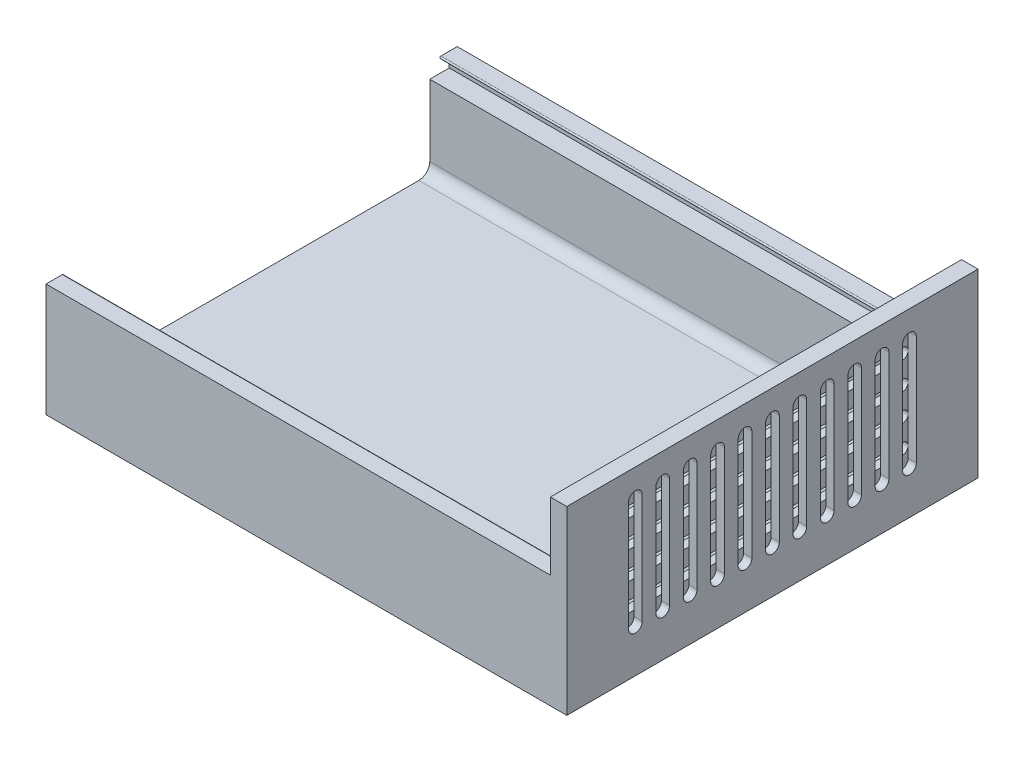
SolidWorks part; units mm, degrees
ref_plane "Front Plane" through (0, 0, 0) normal (0, 0, 1) x (1, 0, 0)
ref_plane "Top Plane" through (0, 0, 0) normal (0, 1, 0) x (1, 0, 0)
ref_plane "Right Plane" through (0, 0, 0) normal (1, 0, 0) x (0, 0, -1)
sketch "Sketch1" plane through (0, 0, 0) normal (0, 1, 0) x (1, 0, 0)
  line L1 (-47.5, -37.5) -> (47.5, -37.5)
  line L2 (-47.5, -37.5) -> (-47.5, 37.5)
  line L3 (-47.5, 37.5) -> (47.5, 37.5)
  line L4 (47.5, -37.5) -> (47.5, 37.5)
  line L5 (-47.5, -37.5) -> (47.5, 37.5) construction
  line L6 (-47.5, 37.5) -> (47.5, -37.5) construction
  point P0 (0, 0)
  dimension "D1" = 95
  dimension "D2" = 75
extrude "Boss-Extrude1" add sketch "Sketch1" along normal blind 3
sketch "Sketch2" plane through (0, 3, 0) normal (0, 1, 0) x (1, 0, 0)
  line L0 (47.5, -37.5) -> (47.5, 37.5) construction
  line L1 (-47.5, 37.5) -> (47.5, 37.5)
  line L2 (-47.5, 37.5) -> (-47.5, 32.5)
  line L3 (-47.5, 32.5) -> (47.5, 32.5)
  line L4 (47.5, 37.5) -> (47.5, 32.5)
  line L6 (-47.5, -37.5) -> (47.5, -37.5)
  line L7 (-47.5, -37.5) -> (-47.5, -32.5)
  line L8 (-47.5, -32.5) -> (47.5, -32.5)
  line L9 (47.5, -37.5) -> (47.5, -32.5)
  dimension "D1" = 5
  dimension "D2" = 5
extrude "Boss-Extrude2" add sketch "Sketch2" along normal blind 15
sketch "Sketch3" plane through (0, 3, 0) normal (0, 1, 0) x (1, 0, 0)
  line L1 (47.5, 37.5) -> (44.5, 37.5)
  line L2 (47.5, 37.5) -> (47.5, -37.5)
  line L3 (47.5, -37.5) -> (44.5, -37.5)
  line L4 (44.5, 37.5) -> (44.5, -37.5)
  line L5 (-47.5, -37.5) -> (47.5, -37.5) construction
  line L6 (47.5, 37.5) -> (-47.5, 37.5) construction
  line L7 (47.5, -32.5) -> (47.5, 32.5) construction
  dimension "D1" = 3
extrude "Boss-Extrude3" add sketch "Sketch3" along normal blind 30
sketch "Sketch4" plane through (47.5, 0, 0) normal (1, 0, 0) x (0, 0, -1)
  line L0 (-37.5, 0) -> (37.5, 0) construction
  line L2 (26.25, 8) -> (26.25, 28)
  line L4 (23.75, 8) -> (23.75, 28)
  line L5 (37.5, 33) -> (37.5, 0) construction
  line L6 (21.25, 8) -> (21.25, 28)
  line L7 (18.75, 8) -> (18.75, 28)
  line L8 (16.25, 8) -> (16.25, 28)
  line L9 (13.75, 8) -> (13.75, 28)
  line L10 (11.25, 8) -> (11.25, 28)
  line L11 (8.75, 8) -> (8.75, 28)
  line L12 (6.25, 8) -> (6.25, 28)
  line L13 (3.75, 8) -> (3.75, 28)
  line L14 (1.25, 8) -> (1.25, 28)
  line L15 (-1.25, 8) -> (-1.25, 28)
  line L16 (-3.75, 8) -> (-3.75, 28)
  line L17 (-6.25, 8) -> (-6.25, 28)
  line L18 (-8.75, 8) -> (-8.75, 28)
  line L19 (-11.25, 8) -> (-11.25, 28)
  line L20 (-13.75, 8) -> (-13.75, 28)
  line L21 (-16.25, 8) -> (-16.25, 28)
  line L22 (-18.75, 8) -> (-18.75, 28)
  line L23 (-21.25, 8) -> (-21.25, 28)
  line L24 (-23.75, 8) -> (-23.75, 28)
  line L25 (-26.25, 8) -> (-26.25, 28)
  arc A0 (26.25, 8) -> (23.75, 8) centre (25, 8) cw
  arc A1 (26.25, 28) -> (23.75, 28) centre (25, 28) ccw
  arc A2 (21.25, 28) -> (18.75, 28) centre (20, 28) ccw
  arc A3 (21.25, 8) -> (18.75, 8) centre (20, 8) cw
  arc A4 (16.25, 28) -> (13.75, 28) centre (15, 28) ccw
  arc A5 (16.25, 8) -> (13.75, 8) centre (15, 8) cw
  arc A6 (11.25, 28) -> (8.75, 28) centre (10, 28) ccw
  arc A7 (11.25, 8) -> (8.75, 8) centre (10, 8) cw
  arc A8 (6.25, 28) -> (3.75, 28) centre (5, 28) ccw
  arc A9 (6.25, 8) -> (3.75, 8) centre (5, 8) cw
  arc A10 (1.25, 28) -> (-1.25, 28) centre (0, 28) ccw
  arc A11 (1.25, 8) -> (-1.25, 8) centre (0, 8) cw
  arc A12 (-3.75, 28) -> (-6.25, 28) centre (-5, 28) ccw
  arc A13 (-3.75, 8) -> (-6.25, 8) centre (-5, 8) cw
  arc A14 (-8.75, 28) -> (-11.25, 28) centre (-10, 28) ccw
  arc A15 (-8.75, 8) -> (-11.25, 8) centre (-10, 8) cw
  arc A16 (-13.75, 28) -> (-16.25, 28) centre (-15, 28) ccw
  arc A17 (-13.75, 8) -> (-16.25, 8) centre (-15, 8) cw
  arc A18 (-18.75, 28) -> (-21.25, 28) centre (-20, 28) ccw
  arc A19 (-18.75, 8) -> (-21.25, 8) centre (-20, 8) cw
  arc A20 (-23.75, 28) -> (-26.25, 28) centre (-25, 28) ccw
  arc A21 (-23.75, 8) -> (-26.25, 8) centre (-25, 8) cw
  dimension "D3" = 8
  dimension "D1" = 2.5
  dimension "D2" = 20
  dimension "D4" = 11.25
  dimension "D5" = 11
extrude "Cut-Extrude1" cut sketch "Sketch4" against normal blind 1.5
sketch "Sketch5" plane through (44.5, 0, 0) normal (-1, 0, 0) x (0, 0, 1)
  line L0 (-26.25, 8) -> (-26.25, 28) construction
  line L1 (-25.25, 24) -> (25.25, 24)
  line L3 (-25.25, 26) -> (25.25, 26)
  line L5 (26.25, 28) -> (26.25, 8) construction
  line L6 (-25.25, 19) -> (25.25, 19)
  line L7 (-25.25, 21) -> (25.25, 21)
  line L8 (-25.25, 14) -> (25.25, 14)
  line L9 (-25.25, 16) -> (25.25, 16)
  line L10 (-25.25, 9) -> (25.25, 9)
  line L11 (-25.25, 11) -> (25.25, 11)
  arc A0 (-25.25, 24) -> (-25.25, 26) centre (-25.25, 25) cw
  arc A1 (25.25, 24) -> (25.25, 26) centre (25.25, 25) ccw
  arc A2 (-3.75, 28) -> (-6.25, 28) centre (-5, 28) ccw construction
  arc A3 (25.25, 19) -> (25.25, 21) centre (25.25, 20) ccw
  arc A4 (-25.25, 19) -> (-25.25, 21) centre (-25.25, 20) cw
  arc A5 (25.25, 14) -> (25.25, 16) centre (25.25, 15) ccw
  arc A6 (-25.25, 14) -> (-25.25, 16) centre (-25.25, 15) cw
  arc A7 (25.25, 9) -> (25.25, 11) centre (25.25, 10) ccw
  arc A8 (-25.25, 9) -> (-25.25, 11) centre (-25.25, 10) cw
  dimension "D1" = 2
  dimension "D2" = 2
  dimension "D3" = 4
extrude "Cut-Extrude2" cut sketch "Sketch5" against normal blind 1.5
sketch "Sketch6" plane through (-47.5, 0, 0) normal (-1, 0, 0) x (0, 0, 1)
  line L0 (37.5, 18) -> (37.5, 20.65)
  line L1 (37.5, 20.65) -> (34.05, 20.65)
  line L3 (34.05, 20.65) -> (36.05, 18.65)
  line L7 (36.05, 18.65) -> (36.05, 18)
  line L8 (32.5, 18) -> (37.5, 18) construction
  line L9 (36.05, 18) -> (37.5, 18)
  line L10 (0, 9.2561) -> (0, -6.358) construction
  line L11 (-36.05, 18) -> (-37.5, 18)
  line L12 (-36.05, 18.65) -> (-36.05, 18)
  line L13 (-34.05, 20.65) -> (-36.05, 18.65)
  line L14 (-37.5, 20.65) -> (-34.05, 20.65)
  line L15 (-37.5, 18) -> (-37.5, 20.65)
  dimension "D1" = 45
  dimension "D2" = 0.65
  dimension "D3" = 1.45
  dimension "D4" = 2.65
extrude "Boss-Extrude4" add sketch "Sketch6" against normal up to surface (95 mm away) up to face at (47.5, 18, -25)
fillet "Fillet1" radius 0.2 2 edges at (-1.5, 20.65, 34.05) (-1.5, 20.65, -34.05)
fillet "Fillet2" radius 2 3 edges at (-1.5, 3, 32.5) (44.5, 3, 0) (-1.5, 3, -32.5)
